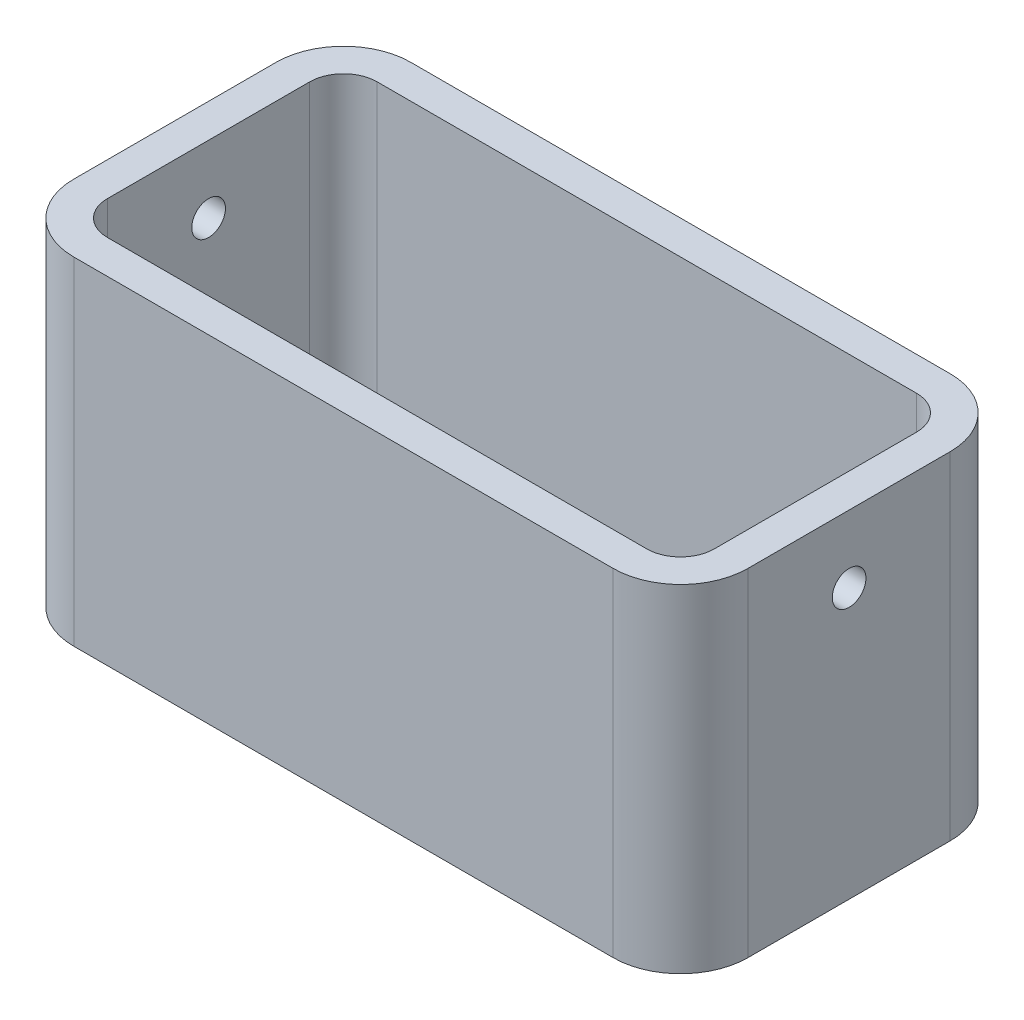
SolidWorks part; units mm, degrees
ref_plane "Front Plane" through (0, 0, 0) normal (0, 0, 1) x (1, 0, 0)
ref_plane "Top Plane" through (0, 0, 0) normal (0, 1, 0) x (1, 0, 0)
ref_plane "Right Plane" through (0, 0, 0) normal (1, 0, 0) x (0, 0, -1)
sketch "Sketch1" plane through (0, 0, 0) normal (0, 1, 0) x (1, 0, 0)
  line L1 (-50, 25) -> (50, 25)
  line L2 (-50, 25) -> (-50, -25)
  line L3 (-50, -25) -> (50, -25)
  line L4 (50, 25) -> (50, -25)
  dimension "D1" = 100
  dimension "D2" = 50
  dimension "D3" = 25
  dimension "D4" = 50
extrude "Boss-Extrude1" add sketch "Sketch1" along normal blind 50
fillet "Fillet1" radius 10 4 edges at (-50, 25, 25) (-50, 25, -25) (50, 25, -25) (50, 25, 25)
shell "Shell1" thickness 5
sketch "Sketch2" plane through (50, 0, 0) normal (1, 0, 0) x (0, 0, -1)
  line L0 (-15, 0) -> (15, 0) construction
  line L2 (-25, 0) -> (-25, 50) construction
  circle A0 centre (0, 40) radius 2.5
  dimension "D1" = 5
  dimension "D2" = 40
  dimension "D3" = 25
extrude "Cut-Extrude1" cut sketch "Sketch2" against normal through all
